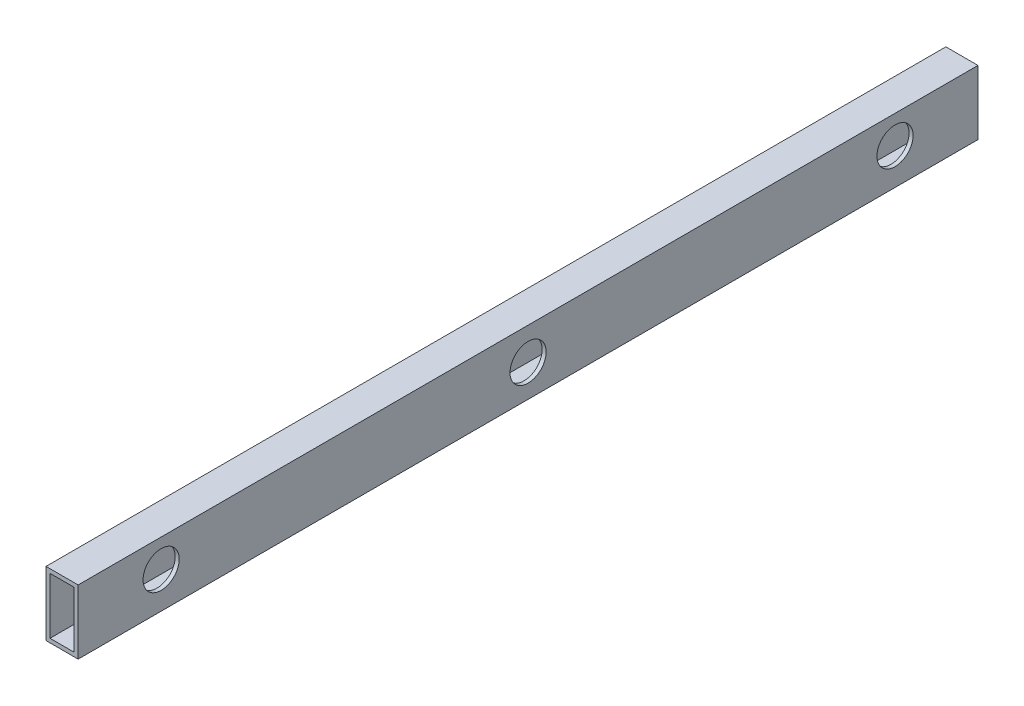
SolidWorks part; units mm, degrees
material "6061-T6 (SS)"
ref_plane "Front Plane" through (0, 0, 0) normal (0, 0, 1) x (1, 0, 0)
ref_plane "Top Plane" through (0, 0, 0) normal (0, 1, 0) x (1, 0, 0)
ref_plane "Right Plane" through (0, 0, 0) normal (1, 0, 0) x (0, 0, -1)
sketch "Sketch1" plane through (0, 0, 0) normal (0, 0, 1) x (1, 0, 0)
  line L0 (266.7, 25.4) -> (241.3, 25.4) construction
  line L1 (241.3, -25.4) -> (241.3, 25.4) construction
  line L2 (266.7, -25.4) -> (241.3, -25.4) construction
  line L3 (266.7, -25.4) -> (266.7, 25.4) construction
  line L4 (266.7, 25.4) -> (241.3, 25.4)
  line L5 (241.3, -25.4) -> (241.3, 25.4)
  line L6 (266.7, -25.4) -> (241.3, -25.4)
  line L7 (266.7, -25.4) -> (266.7, 25.4)
  line L8 (263.525, 22.225) -> (244.475, 22.225)
  line L9 (244.475, -22.225) -> (244.475, 22.225)
  line L10 (263.525, -22.225) -> (244.475, -22.225)
  line L11 (263.525, -22.225) -> (263.525, 22.225)
  dimension "D1" = 3.175
extrude "Boss-Extrude1" add sketch "Sketch1" along normal up to vertex (355.6 mm away)
sketch "Sketch3" plane through (0, 0, 0) normal (0, 1, 0) x (1, 0, 0)
  line L0 (266.7, -381) -> (221.678, -335.978) construction
  line L1 (266.7, -381) -> (221.678, -335.978)
  line L2 (221.678, -335.978) -> (221.678, -381)
  line L3 (0, -381) -> (266.7, -381) construction
  line L4 (221.678, -381) -> (266.7, -381)
extrude "Cut-Extrude2" [suppressed] cut sketch "Sketch3" against normal through all both and the other way through all
mirror "Mirror1" about plane through (0, 0, 0) normal (0, 0, 1) of "Boss-Extrude1", "Cut-Extrude2"
sketch "Sketch2" plane through (0, 0, 0) normal (1, 0, 0) x (0, 0, -1)
  circle A0 centre (290.0074, 3.175) radius 14.2875 construction
  circle A1 centre (0, 0) radius 14.2875 construction
  circle A2 centre (-290.0074, 3.175) radius 14.2875 construction
  circle A3 centre (290.0074, 3.175) radius 14.2875
  circle A4 centre (0, 0) radius 14.2875
  circle A5 centre (-290.0074, 3.175) radius 14.2875
extrude "Cut-Extrude1" cut sketch "Sketch2" along normal through all
